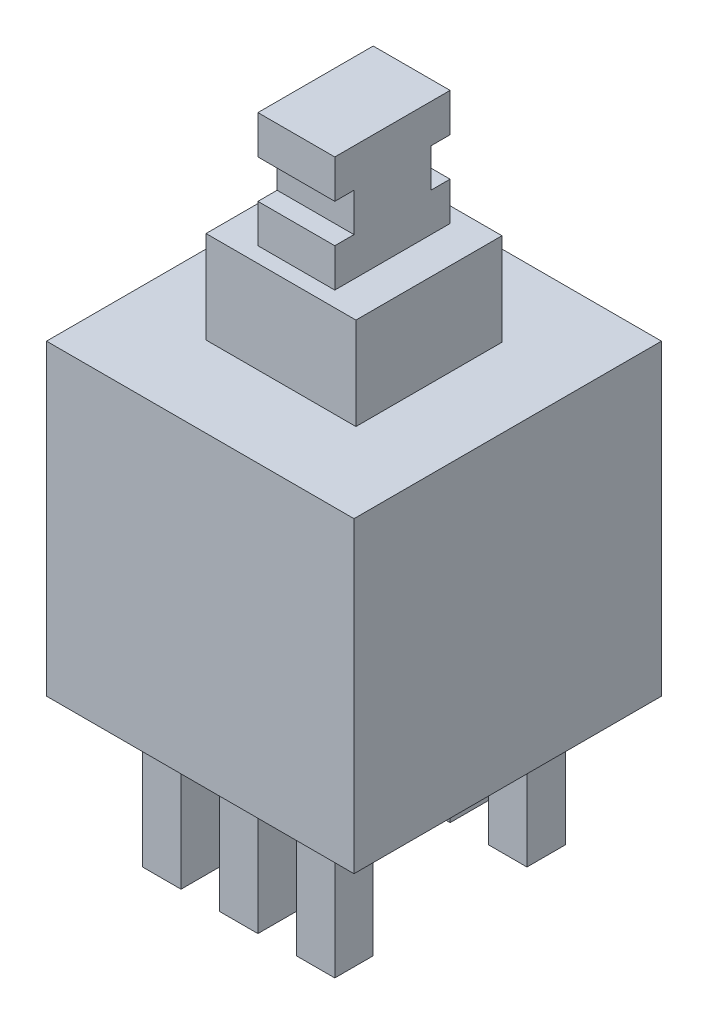
SolidWorks part; units mm, degrees
ref_plane "Front Plane" through (0, 0, 0) normal (0, 0, 1) x (1, 0, 0)
ref_plane "Top Plane" through (0, 0, 0) normal (0, 1, 0) x (1, 0, 0)
ref_plane "Right Plane" through (0, 0, 0) normal (1, 0, 0) x (0, 0, -1)
sketch "Sketch1" plane through (0, 0, 0) normal (0, 1, 0) x (1, 0, 0)
  line L1 (-4, -4) -> (4, -4)
  line L2 (-4, -4) -> (-4, 4)
  line L3 (-4, 4) -> (4, 4)
  line L4 (4, -4) -> (4, 4)
  line L5 (-4, -4) -> (4, 4) construction
  line L6 (-4, 4) -> (4, -4) construction
  point P0 (0, 0)
  dimension "D1" = 8
extrude "Boss-Extrude1" add sketch "Sketch1" along normal blind 8
sketch "Sketch2" plane through (0, 8, 0) normal (0, 1, 0) x (1, 0, 0)
  line L1 (-1.95, -1.9) -> (1.95, -1.9)
  line L2 (-1.95, -1.9) -> (-1.95, 1.9)
  line L3 (-1.95, 1.9) -> (1.95, 1.9)
  line L4 (1.95, -1.9) -> (1.95, 1.9)
  line L5 (-1.95, -1.9) -> (1.95, 1.9) construction
  line L6 (-1.95, 1.9) -> (1.95, -1.9) construction
  point P0 (0, 0)
  dimension "D1" = 3.9
  dimension "D2" = 3.8
extrude "Boss-Extrude2" add sketch "Sketch2" along normal blind 2.4
sketch "Sketch3" plane through (0, 10.4, 0) normal (0, 1, 0) x (1, 0, 0)
  line L1 (-1, -1.5) -> (1, -1.5)
  line L2 (-1, -1.5) -> (-1, 1.5)
  line L3 (-1, 1.5) -> (1, 1.5)
  line L4 (1, -1.5) -> (1, 1.5)
  line L5 (-1, -1.5) -> (1, 1.5) construction
  line L6 (-1, 1.5) -> (1, -1.5) construction
  point P0 (0, 0)
  dimension "D1" = 2
  dimension "D2" = 3
extrude "Boss-Extrude3" add sketch "Sketch3" along normal blind 3
sketch "Sketch4" plane through (0, 0, 0) normal (0, -1, 0) x (1, 0, 0)
  line L0 (-0.5, 3) -> (-0.5, 2)
  line L1 (-2.5, 3) -> (-1.5, 3)
  line L2 (-2.5, 3) -> (-2.5, 2)
  line L3 (-2.5, 2) -> (-1.5, 2)
  line L4 (-1.5, 3) -> (-1.5, 2)
  line L5 (-0.5, 3) -> (0.5, 3)
  line L6 (0.5, 3) -> (0.5, 2)
  line L7 (-0.5, 2) -> (0.5, 2)
  line L8 (1.5, 3) -> (1.5, 2)
  line L9 (1.5, 3) -> (2.5, 3)
  line L10 (2.5, 3) -> (2.5, 2)
  line L11 (1.5, 2) -> (2.5, 2)
  line L12 (-0.5, -2) -> (-0.5, -3)
  line L13 (-0.5, -2) -> (0.5, -2)
  line L14 (0.5, -2) -> (0.5, -3)
  line L15 (-0.5, -3) -> (0.5, -3)
  line L16 (1.5, -2) -> (1.5, -3)
  line L17 (1.5, -2) -> (2.5, -2)
  line L18 (2.5, -2) -> (2.5, -3)
  line L19 (1.5, -3) -> (2.5, -3)
  line L20 (-2.5, -2) -> (-2.5, -3)
  line L21 (-2.5, -2) -> (-1.5, -2)
  line L22 (-1.5, -2) -> (-1.5, -3)
  line L23 (-2.5, -3) -> (-1.5, -3)
  point P4 (-2, 2)
  point P6 (-2.5, 2.5)
  point P7 (2.5, -2.5)
  point P8 (2, -2)
  point P29 (2, 2)
  dimension "D1" = 2
  dimension "D2" = 1
  dimension "D3" = 1
  dimension "D4" = 2.5
  dimension "D7" = 2.5
  dimension "D8" = 2
  dimension "D9" = 2
  dimension "D5" = 3
  dimension "D6" = 2
extrude "Boss-Extrude4" add sketch "Sketch4" along normal blind 3.6
sketch "Sketch5" plane through (1, 0, 0) normal (1, 0, 0) x (0, 0, -1)
  line L0 (-1.5, 13.4) -> (-1.5, 10.4) construction
  line L1 (-1.5, 12.4) -> (-1, 12.4)
  line L2 (-1.5, 12.4) -> (-1.5, 11.4)
  line L3 (-1.5, 11.4) -> (-1, 11.4)
  line L4 (-1, 12.4) -> (-1, 11.4)
  line L5 (1.5, 13.4) -> (1.5, 10.4) construction
  line L6 (1.5, 12.4) -> (1, 12.4)
  line L7 (1.5, 12.4) -> (1.5, 11.4)
  line L8 (1.5, 11.4) -> (1, 11.4)
  line L9 (1, 12.4) -> (1, 11.4)
  line L10 (-1.5, 13.4) -> (1.5, 13.4) construction
  dimension "D1" = 0.5
  dimension "D2" = 1
  dimension "D3" = 1
extrude "Cut-Extrude1" cut sketch "Sketch5" against normal through all
ref_plane "MAX" through (0, 13.5, 0) normal (0, 1, 0) x (1, 0, 0)
ref_plane "MIN" through (0, 11, 0) normal (0, 1, 0) x (1, 0, 0)
equation "\"D7@Sketch4\"=\"D4@Sketch4\""
equation "\"D8@Sketch4\"=\"D1@Sketch4\""
equation "\"D9@Sketch4\"=\"D1@Sketch4\""
